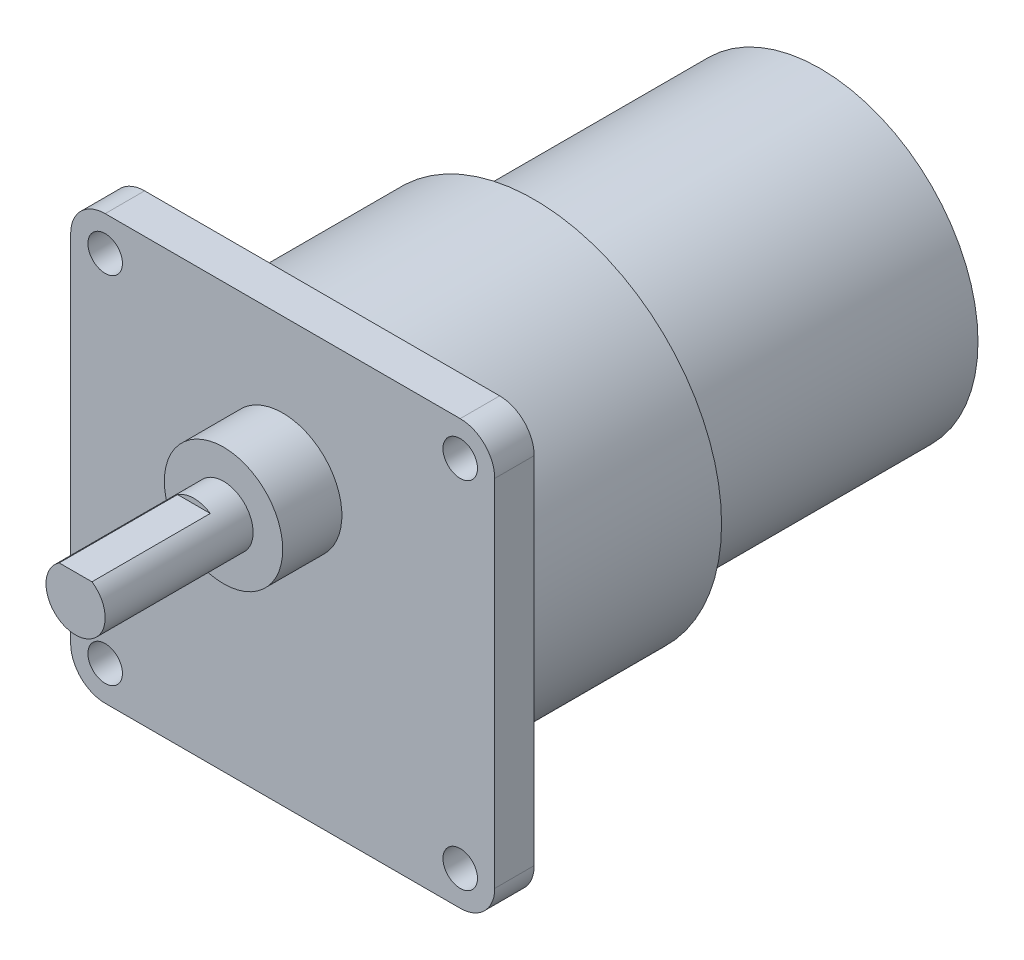
SolidWorks part; units mm, degrees
ref_plane "정면" through (0, 0, 0) normal (0, 0, 1) x (1, 0, 0)
ref_plane "윗면" through (0, 0, 0) normal (0, 1, 0) x (1, 0, 0)
ref_plane "우측면" through (0, 0, 0) normal (1, 0, 0) x (0, 0, -1)
sketch "스케치1" plane through (0, 0, 0) normal (0, 0, 1) x (1, 0, 0)
  line L0 (-48.9332, 0) -> (45.7433, 0) construction
  line L1 (0, -42.4896) -> (0, 44.1484) construction
  line L3 (-21.5, -21.5) -> (21.5, -21.5)
  line L4 (-21.5, -21.5) -> (-21.5, 21.5)
  line L5 (-21.5, 21.5) -> (21.5, 21.5)
  line L6 (21.5, -21.5) -> (21.5, 21.5)
  line L7 (-21.5, -21.5) -> (21.5, 21.5) construction
  line L8 (-21.5, 21.5) -> (21.5, -21.5) construction
  point P5 (0, 0)
  dimension "D1" = 43
  dimension "D2" = 43
extrude "보스-돌출1" add sketch "스케치1" along normal blind 4
fillet "필렛1" radius 3.5 4 edges at (21.5, -21.5, 2) (-21.5, -21.5, 2) (-21.5, 21.5, 2) (21.5, 21.5, 2)
sketch "스케치2" plane through (0, 0, 4) normal (0, 0, 1) x (1, 0, 0)
  line L0 (-51.5792, 0) -> (67.0414, 0) construction
  line L1 (0, 47.079) -> (0, -52.1562) construction
  circle A0 centre (18, 18) radius 1.75
  circle A1 centre (-18, 18) radius 1.75
  circle A2 centre (18, -18) radius 1.75
  circle A3 centre (-18, -18) radius 1.75
  dimension "D3" = 3.5
  dimension "D1" = 36
  dimension "D2" = 36
extrude "컷-돌출1" cut sketch "스케치2" against normal through all
sketch "스케치3" plane through (0, 0, 4) normal (0, 0, 1) x (1, 0, 0)
  line L0 (-34.862, 0) -> (41.5828, 0) construction
  line L1 (0, 33.3532) -> (0, -35.5399) construction
  circle A0 centre (0, 7) radius 6
  dimension "D2" = 12
  dimension "D1" = 7
extrude "보스-돌출2" add sketch "스케치3" along normal blind 6
sketch "스케치4" plane through (0, 0, 10) normal (0, 0, 1) x (1, 0, 0)
  line L0 (-14.266, 0) -> (16.1338, 0) construction
  line L1 (0, -14.8135) -> (0, 18.549) construction
  line L2 (-12.3982, 7) -> (12.3982, 7) construction
  circle A0 centre (0, 7) radius 3
  dimension "D2" = 6
  dimension "D1" = 7
extrude "보스-돌출3" add sketch "스케치4" along normal blind 15
sketch "스케치5" plane through (0, 0, 25) normal (0, 0, 1) x (1, 0, 0)
  line L0 (-1.6583, 9.5) -> (1.6583, 9.5)
  circle A0 centre (0, 7) radius 3 construction
  arc A1 (1.6583, 9.5) -> (-1.6583, 9.5) centre (0, 7) ccw
  dimension "D1" = 2.5
extrude "컷-돌출2" cut sketch "스케치5" against normal blind 12
sketch "스케치6" plane through (0, 0, 0) normal (0, 0, -1) x (-1, 0, 0)
  circle A0 centre (0, 0) radius 19
  dimension "D1" = 38
extrude "보스-돌출4" add sketch "스케치6" along normal blind 21.5
sketch "스케치7" plane through (0, 0, -21.5) normal (0, 0, -1) x (-1, 0, 0)
  circle A0 centre (0, 0) radius 16
  dimension "D1" = 32
extrude "보스-돌출5" add sketch "스케치7" along normal blind 29
